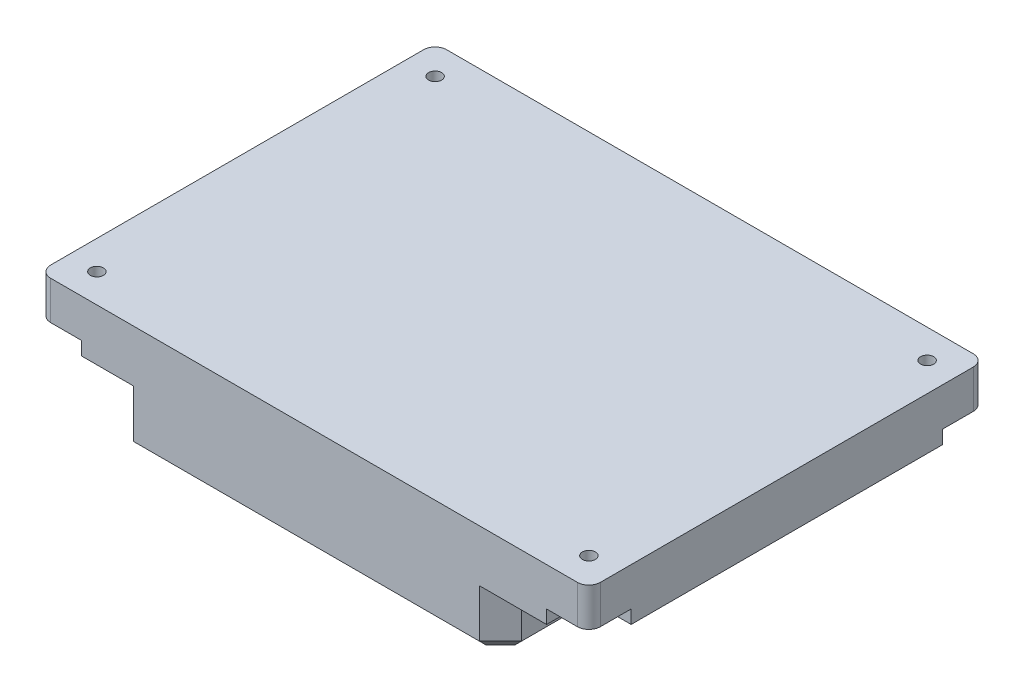
SolidWorks part; units mm, degrees
ref_plane "Front Plane" through (0, 0, 0) normal (0, 0, 1) x (1, 0, 0)
ref_plane "Top Plane" through (0, 0, 0) normal (0, 1, 0) x (1, 0, 0)
ref_plane "Right Plane" through (0, 0, 0) normal (1, 0, 0) x (0, 0, -1)
ref_plane "Plane1" through (0, 3, 0) normal (0, 1, 0) x (1, 0, 0)
sketch "Sketch1" plane through (0, 3, 0) normal (0, 1, 0) x (1, 0, 0)
  line L0 (71.5, -48.5) -> (71.5, 48.5)
  line L1 (68.5, 51.5) -> (-68.5, 51.5)
  line L2 (-71.5, 48.5) -> (-71.5, -48.5)
  line L3 (-68.5, -51.5) -> (68.5, -51.5)
  arc A0 (68.5, -51.5) -> (71.5, -48.5) centre (68.5, -48.5) ccw
  arc A1 (71.5, 48.5) -> (68.5, 51.5) centre (68.5, 48.5) ccw
  arc A2 (-68.5, 51.5) -> (-71.5, 48.5) centre (-68.5, 48.5) ccw
  arc A3 (-71.5, -48.5) -> (-68.5, -51.5) centre (-68.5, -48.5) ccw
  circle A22 centre (-64, 44) radius 1.7
  circle A34 centre (-64, -44) radius 1.7
  circle A40 centre (64, -44) radius 1.7
  circle A55 centre (64, 44) radius 1.7
extrude "Boss-Extrude1" add sketch "Sketch1" against normal blind 13.5
sketch "Sketch2" plane through (0, -10.5, 0) normal (0, -1, 0) x (1, 0, 0)
  line L0 (-71.5, -40.5) -> (-63, -40.5)
  line L1 (-71.5, -48.5) -> (-71.5, 48.5) construction
  line L2 (-60.5, -43) -> (-60.5, -51.5)
  line L3 (68.5, -51.5) -> (-68.5, -51.5) construction
  line L4 (-71.5, -40.5) -> (-71.5, -48.5)
  line L5 (-68.5, -51.5) -> (-60.5, -51.5)
  line L6 (-71.5, 40.5) -> (-63, 40.5)
  line L7 (-60.5, 43) -> (-60.5, 51.5)
  line L8 (-68.5, 51.5) -> (68.5, 51.5) construction
  line L9 (-71.5, 48.5) -> (-71.5, 40.5)
  line L10 (60.5, 51.5) -> (60.5, 43)
  line L11 (-68.5, 51.5) -> (-60.5, 51.5)
  line L12 (60.5, -51.5) -> (60.5, -43)
  line L13 (63, -40.5) -> (71.5, -40.5)
  line L14 (71.5, 48.5) -> (71.5, -48.5) construction
  line L15 (71.5, -40.5) -> (71.5, -48.5)
  line L16 (-63, -40.5) -> (-60.5, -43)
  line L17 (63, 40.5) -> (71.5, 40.5)
  line L18 (60.5, -43) -> (63, -40.5)
  line L19 (60.5, 43) -> (63, 40.5)
  line L20 (-63, 40.5) -> (-60.5, 43)
  line L21 (60.5, 51.5) -> (68.5, 51.5)
  line L22 (71.5, 48.5) -> (71.5, 40.5)
  line L23 (60.5, -51.5) -> (68.5, -51.5)
  arc A1 (-71.5, -48.5) -> (-68.5, -51.5) centre (-68.5, -48.5) ccw construction
  arc A3 (-68.5, 51.5) -> (-71.5, 48.5) centre (-68.5, 48.5) ccw construction
  arc A8 (71.5, 48.5) -> (68.5, 51.5) centre (68.5, 48.5) ccw construction
  arc A9 (-68.5, 51.5) -> (-71.5, 48.5) centre (-68.5, 48.5) ccw
  arc A10 (68.5, -51.5) -> (71.5, -48.5) centre (68.5, -48.5) ccw construction
  arc A11 (71.5, 48.5) -> (68.5, 51.5) centre (68.5, 48.5) ccw
  arc A12 (-71.5, -48.5) -> (-68.5, -51.5) centre (-68.5, -48.5) ccw
  arc A13 (68.5, -51.5) -> (71.5, -48.5) centre (68.5, -48.5) ccw
  point P1 (-60.5, -40.5)
  point P8 (-60.5, 40.5)
  point P15 (60.5, -40.5)
  point P24 (60.5, 40.5)
  dimension "D1" = 11
  dimension "D2" = 11
extrude "Cut-Extrude2" cut sketch "Sketch2" against normal blind 3.5
sketch "Sketch3" plane through (0, -10.5, 0) normal (0, -1, 0) x (1, 0, 0)
  line L0 (-52.5, 46) -> (-52.5, -32)
  line L1 (-60.5, 51.5) -> (60.5, 51.5) construction
  line L2 (-47, -37.5) -> (43, -37.5)
  line L3 (48.5, -32) -> (48.5, 46)
  line L4 (43, 51.5) -> (-47, 51.5)
  line L5 (60.5, -51.5) -> (-60.5, -51.5) construction
  line L6 (-71.5, -40.5) -> (-71.5, 40.5) construction
  line L7 (71.5, 40.5) -> (71.5, -40.5) construction
  line L8 (-52.5, -32) -> (-47, -37.5)
  line L9 (-47, 51.5) -> (-52.5, 46)
  line L10 (48.5, 46) -> (43, 51.5)
  line L11 (43, -37.5) -> (48.5, -32)
  point P0 (-52.5, 51.5)
  point P1 (-52.5, -37.5)
  point P5 (48.5, -37.5)
  point P6 (48.5, 51.5)
  dimension "D1" = 14
  dimension "D2" = 19
  dimension "D3" = 23
extrude "Boss-Extrude2" add sketch "Sketch3" along normal blind 15.5
chamfer "Chamfer1" distance 3 angle 45 8 edges at (-2, -26, -37.5) (-49.75, -26, -34.75) (48.5, -26, 7) (45.75, -26, -34.75) (45.75, -26, 48.75) (-2, -26, 51.5) (-49.75, -26, 48.75) (-52.5, -26, 7)
sketch "Sketch4" plane through (0, -26, 0) normal (0, -1, 0) x (1, 0, 0)
  line L0 (-43.1186, 26.8827) -> (37.5921, 26.8827) construction
  text T0 "Control Hub" font "Century Gothic" height 10
